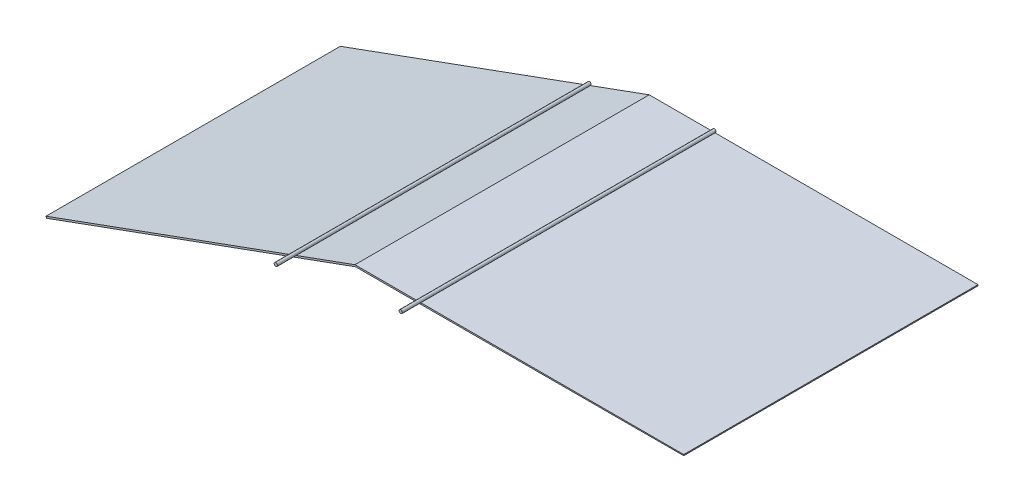
SolidWorks part; units mm, degrees
ref_plane "Plano frontal" through (0, 0, 0) normal (0, 0, 1) x (1, 0, 0)
ref_plane "Plano superior" through (0, 0, 0) normal (0, 1, 0) x (1, 0, 0)
ref_plane "Plano direito" through (0, 0, 0) normal (1, 0, 0) x (0, 0, -1)
sketch "Esboço10" plane through (0, 0, 0) normal (0, 0, 1) x (1, 0, 0)
  line L0 (943.2935, 0) -> (-56.7065, 0)
  line L1 (-56.7065, 0) -> (-996.3992, -342.0201)
  line L2 (-996.3992, -342.0201) -> (-994.6891, -346.7186)
  line L3 (-994.6891, -346.7186) -> (-54.9964, -4.6985)
  line L4 (-54.9964, -4.6985) -> (943.2935, -3.1566)
  line L5 (943.2935, -3.1566) -> (943.2935, 0)
  dimension "D1" = 20
  dimension "D2" = 90
extrude "Ressalto-extrusão3" add sketch "Esboço10" along normal blind 895
sketch "Esboço12" plane through (0, 0, 0) normal (0, 0, -1) x (-1, 0, 0)
  line L0 (-943.2935, 0) -> (56.7065, 0) construction
  line L1 (56.7065, 0) -> (996.3992, -342.0201) construction
  circle A0 centre (-141.5315, 5) radius 5
  circle A1 centre (238.3715, -60.7998) radius 5
  dimension "D1" = 5
  dimension "D2" = 5
extrude "Ressalto-extrusão4" add sketch "Esboço12" against normal blind 954 separate body
